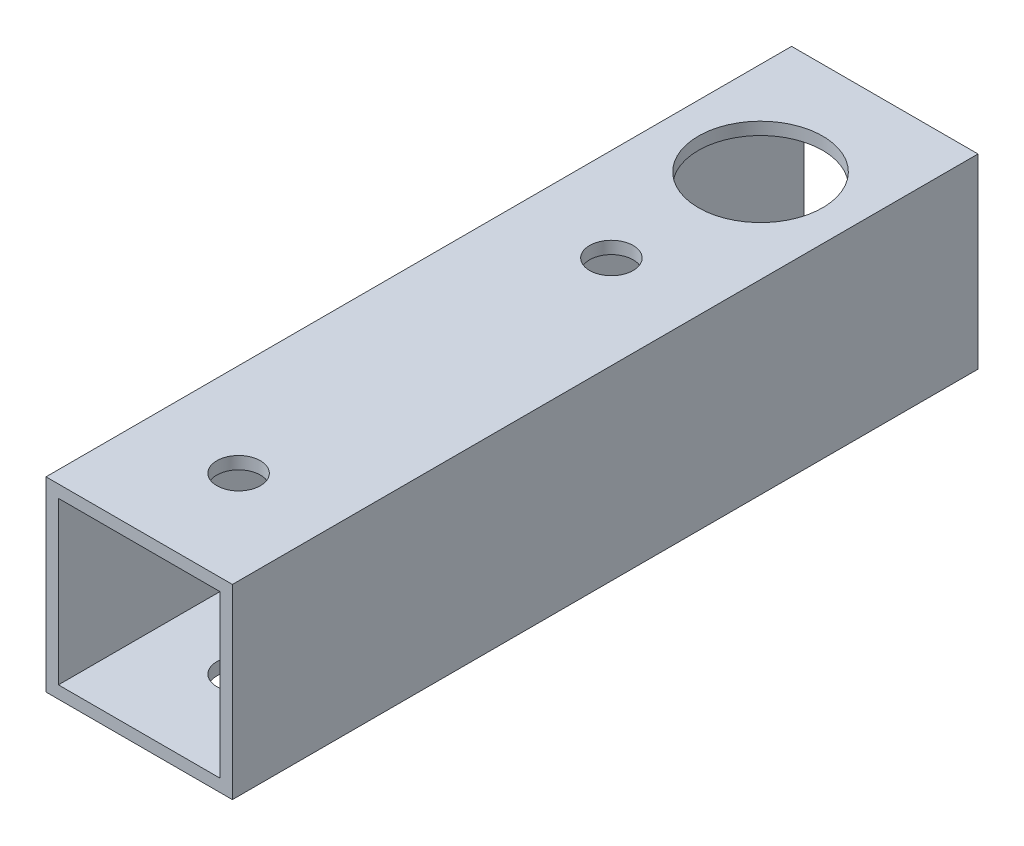
SolidWorks part; units mm, degrees
material "Alu"
ref_plane "Ebene vorne" through (0, 0, 0) normal (0, 0, 1) x (1, 0, 0)
ref_plane "Ebene oben" through (0, 0, 0) normal (0, 1, 0) x (1, 0, 0)
ref_plane "Ebene rechts" through (0, 0, 0) normal (1, 0, 0) x (0, 0, -1)
sketch "Skizze1" plane through (0, 0, 0) normal (0, 0, 1) x (1, 0, 0)
  line L1 (7.5, -7.5) -> (-7.5, -7.5)
  line L2 (7.5, -7.5) -> (7.5, 7.5)
  line L3 (7.5, 7.5) -> (-7.5, 7.5)
  line L4 (-7.5, -7.5) -> (-7.5, 7.5)
  line L5 (7.5, -7.5) -> (-7.5, 7.5) construction
  line L6 (7.5, 7.5) -> (-7.5, -7.5) construction
  point P0 (0, 0)
  dimension "D1" = 15
extrude "Linear-Austragen-Dünn1" add sketch "Skizze1" along normal mid plane 60 thin
sketch "Skizze2" plane through (0, 7.5, 0) normal (0, 1, 0) x (1, 0, 0)
  line L0 (0, -30) -> (0, 30) construction
  line L1 (7.5, -30) -> (-7.5, -30) construction
  line L2 (7.5, 30) -> (-7.5, 30) construction
  circle A0 centre (0, -22) radius 1.75
  circle A1 centre (0, 8) radius 1.75
  circle A2 centre (0, 20) radius 5
  dimension "D1" = 3.5
  dimension "D4" = 10
  dimension "D2" = 30
  dimension "D3" = 8
  dimension "D5" = 10
extrude "Schnitt-Linear austragen1" cut sketch "Skizze2" against normal blind 17
